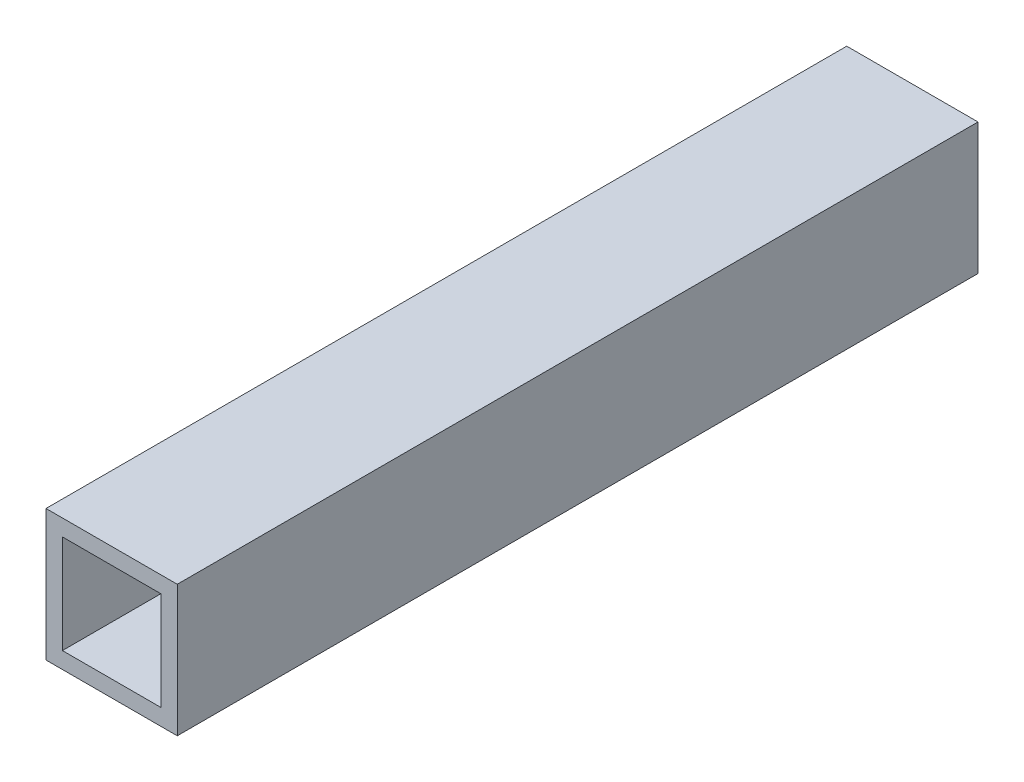
SolidWorks part; units mm, degrees
ref_plane "Front Plane" through (0, 0, 0) normal (0, 0, 1) x (1, 0, 0)
ref_plane "Top Plane" through (0, 0, 0) normal (0, 1, 0) x (1, 0, 0)
ref_plane "Right Plane" through (0, 0, 0) normal (1, 0, 0) x (0, 0, -1)
sketch "Sketch1" plane through (0, 0, 0) normal (0, 0, 1) x (1, 0, 0)
  line L1 (0, 0) -> (-25.4, 0)
  line L2 (0, 0) -> (0, 25.4)
  line L3 (0, 25.4) -> (-25.4, 25.4)
  line L4 (-25.4, 0) -> (-25.4, 25.4)
  line L5 (-22.225, 22.225) -> (-3.175, 22.225)
  line L6 (-22.225, 22.225) -> (-22.225, 3.175)
  line L7 (-22.225, 3.175) -> (-3.175, 3.175)
  line L8 (-3.175, 22.225) -> (-3.175, 3.175)
  dimension "D1" = 25.4
  dimension "D2" = 25.4
  dimension "D3" = 3.175
  dimension "D4" = 3.175
  dimension "D5" = 3.175
  dimension "D6" = 3.175
extrude "Boss-Extrude1" add sketch "Sketch1" along normal blind 154.94
